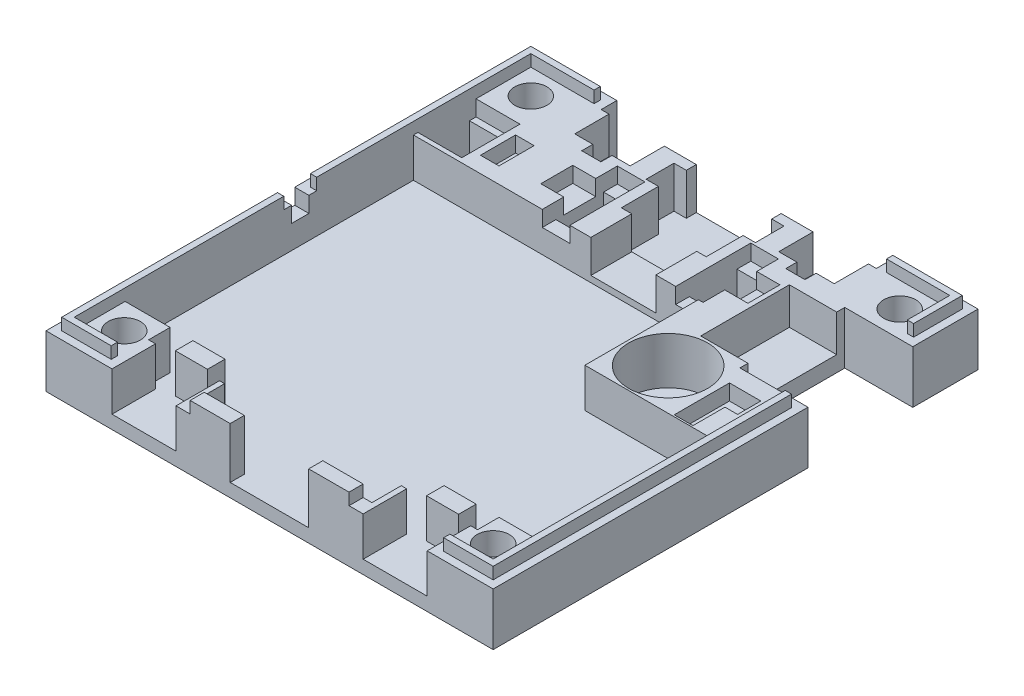
SolidWorks part; units mm, degrees
ref_plane "前视基准面" through (0, 0, 0) normal (0, 0, 1) x (1, 0, 0)
ref_plane "上视基准面" through (0, 0, 0) normal (0, 1, 0) x (1, 0, 0)
ref_plane "右视基准面" through (0, 0, 0) normal (1, 0, 0) x (0, 0, -1)
other "Configuration Table"
sketch "草图1" plane through (0, 0, 0) normal (0, 1, 0) x (1, 0, 0)
  line L1 (-21.6816, 44.1559) -> (35.2931, 44.1559)
  line L2 (-21.6816, 44.1559) -> (-21.6816, -17.6188)
  line L3 (-21.6816, -17.6188) -> (35.2931, -17.6188)
  line L4 (35.2931, 44.1559) -> (35.2931, -17.6188)
  line L10 (-19.6816, -15.6188) -> (33.2931, -15.6188)
  line L11 (-19.6816, 42.1559) -> (-19.6816, -15.6188)
  line L12 (33.2931, 42.1559) -> (-19.6816, 42.1559)
  line L13 (33.2931, -15.6188) -> (33.2931, 42.1559)
  line L14 (-19.6816, -15.6188) -> (33.2931, -15.6188) construction
  line L15 (-19.6816, 42.1559) -> (-19.6816, -15.6188) construction
  line L16 (33.2931, 42.1559) -> (-19.6816, 42.1559) construction
  line L17 (33.2931, -15.6188) -> (33.2931, 42.1559) construction
  point P0 (0, 0)
  dimension "D2" = 2
  dimension "D3" = 2
  dimension "D4" = 2
  dimension "D5" = 2
  dimension "D1" = 0
extrude "凸台-拉伸1" add sketch "草图1" along normal blind 6.7
sketch "草图2" plane through (0, 6.7, 0) normal (0, 1, 0) x (1, 0, 0)
  line L0 (25.7718, 29.0769) -> (25.7718, 24.5122) construction
  line L1 (25.9439, 22.6915) -> (33.2931, 22.6915) construction
  line L2 (33.2931, 35.6455) -> (25.8931, 35.6455) construction
  line L3 (25.7718, 29.0769) -> (25.7718, 24.5122) construction
  line L4 (25.9439, 22.6915) -> (33.2931, 22.6915) construction
  line L5 (33.2931, 35.6455) -> (25.8931, 35.6455) construction
  line L6 (35.2931, 22.4915) -> (26.6238, 22.4915)
  line L7 (35.2931, -17.6188) -> (35.2931, 44.1559) construction
  line L8 (26.6238, 22.4915) -> (26.6238, 35.8455)
  line L9 (26.6238, 35.8455) -> (35.2931, 35.8455)
  line L10 (35.2931, 22.4915) -> (35.2931, 35.8455)
  dimension "D1" = 0.2
  dimension "D2" = 0.2
  dimension "D3" = 0.3
extrude "切除-拉伸1" cut sketch "草图2" against normal through all
sketch "草图3" plane through (0, 6.7, 0) normal (0, 1, 0) x (1, 0, 0)
  line L0 (26.6238, 23.5185) -> (20.5988, 23.5185)
  line L1 (26.6238, 35.8455) -> (26.6238, 22.4915) construction
  line L2 (20.5988, 23.5185) -> (20.5988, 34.8186)
  line L3 (20.5988, 34.8186) -> (26.6238, 34.8186)
  line L4 (26.6238, 34.8186) -> (26.6238, 23.5185)
  line L5 (20.8988, 32.2066) -> (20.8988, 37.3055) construction
  line L6 (21.9488, 34.5186) -> (23.1488, 34.5186) construction
  line L7 (23.1488, 23.8185) -> (21.9488, 23.8185) construction
  dimension "D1" = 0.3
  dimension "D2" = 0.3
  dimension "D3" = 0.3
extrude "切除-拉伸2" cut sketch "草图3" against normal blind 4.7
sketch "草图4" plane through (0, 6.7, 0) normal (0, 1, 0) x (1, 0, 0)
  circle A0 centre (21.8058, 18.1684) radius 5.03
  arc A2 (20.8058, 18.1684) -> (22.8058, 18.1684) centre (21.8058, 18.1684) ccw
  arc A3 (22.8058, 18.1684) -> (20.8058, 18.1684) centre (21.8058, 18.1684) ccw
  arc A4 (20.8058, 18.1684) -> (22.8058, 18.1684) centre (21.8058, 18.1684) ccw construction
  arc A5 (22.8058, 18.1684) -> (20.8058, 18.1684) centre (21.8058, 18.1684) ccw construction
  spline S2 degree 2 poles (1990.58, 337.6383) (3.6905, 85.0515) (17.1696, 17.246) (17.2603, 16.7899) (17.4386, 16.3592) (17.6165, 15.9296) (17.8754, 15.542) (18.1338, 15.1553) (18.4633, 14.8257) (18.7921, 14.4969) (19.1796, 14.2379) (19.5662, 13.9795) (19.9968, 13.801) (20.4264, 13.623) (20.8836, 13.532) (21.3397, 13.4413) (21.8058, 13.4412) (22.2708, 13.4412) (22.7279, 13.532) (23.184, 13.6227) (23.6147, 13.801) (24.0443, 13.9789) (24.4319, 14.2379) (24.8186, 14.4962) (25.1482, 14.8257) (25.4771, 15.1545) (25.7361, 15.542) (25.9945, 15.9286) (26.1729, 16.3592) (26.3509, 16.7888) (26.4419, 17.246) (39.9075, 84.9009) (-1942.9695, 361.3773) knots -9.212791 -9.212791 -9.212791 0.0625 0.0625 0.125 0.125 0.1875 0.1875 0.25 0.25 0.3125 0.3125 0.375 0.375 0.4375 0.4375 0.5 0.5 0.5625 0.5625 0.625 0.625 0.6875 0.6875 0.75 0.75 0.8125 0.8125 0.875 0.875 0.9375 0.9375 10.203452 10.203452 10.203452 only from (17.0788, 18.1682) to (26.5327, 18.1682)
  spline S3 degree 2 poles (-1946.9685, -301.3019) (39.921, -48.7151) (26.4419, 19.0904) (26.3512, 19.5464) (26.1729, 19.9771) (25.995, 20.4067) (25.7361, 20.7943) (25.4778, 21.181) (25.1482, 21.5106) (24.8194, 21.8395) (24.4319, 22.0985) (24.0453, 22.3569) (23.6147, 22.5353) (23.1851, 22.7133) (22.7279, 22.8043) (22.2719, 22.8951) (21.8058, 22.8951) (21.3408, 22.8952) (20.8836, 22.8043) (20.4275, 22.7136) (19.9968, 22.5353) (19.5672, 22.3574) (19.1796, 22.0985) (18.7929, 21.8402) (18.4633, 21.5106) (18.1345, 21.1819) (17.8754, 20.7943) (17.6171, 20.4077) (17.4386, 19.9771) (17.2606, 19.5475) (17.1696, 19.0904) (3.7041, -48.5645) (1986.581, -325.0409) knots -9.212791 -9.212791 -9.212791 0.0625 0.0625 0.125 0.125 0.1875 0.1875 0.25 0.25 0.3125 0.3125 0.375 0.375 0.4375 0.4375 0.5 0.5 0.5625 0.5625 0.625 0.625 0.6875 0.6875 0.75 0.75 0.8125 0.8125 0.875 0.875 0.9375 0.9375 10.203452 10.203452 10.203452 only from (26.5327, 18.1682) to (17.0788, 18.1682)
  spline S4 degree 2 poles (17.0788, 18.1682) (17.0788, 17.7029) (17.1696, 17.246) (17.2603, 16.7899) (17.4386, 16.3592) (17.6165, 15.9296) (17.8754, 15.542) (18.1338, 15.1553) (18.4633, 14.8257) (18.7921, 14.4969) (19.1796, 14.2379) (19.5662, 13.9795) (19.9968, 13.801) (20.4264, 13.623) (20.8836, 13.532) (21.3397, 13.4413) (21.8058, 13.4412) (22.2708, 13.4412) (22.7279, 13.532) (23.184, 13.6227) (23.6147, 13.801) (24.0443, 13.9789) (24.4319, 14.2379) (24.8186, 14.4962) (25.1482, 14.8257) (25.4771, 15.1545) (25.7361, 15.542) (25.9945, 15.9286) (26.1729, 16.3592) (26.3509, 16.7888) (26.4419, 17.246) (26.5327, 17.7023) (26.5327, 18.1682) knots 0 0 0 0.0625 0.0625 0.125 0.125 0.1875 0.1875 0.25 0.25 0.3125 0.3125 0.375 0.375 0.4375 0.4375 0.5 0.5 0.5625 0.5625 0.625 0.625 0.6875 0.6875 0.75 0.75 0.8125 0.8125 0.875 0.875 0.9375 0.9375 1 1 1 construction
  spline S5 degree 2 poles (26.5327, 18.1682) (26.5327, 18.6335) (26.4419, 19.0904) (26.3512, 19.5464) (26.1729, 19.9771) (25.995, 20.4067) (25.7361, 20.7943) (25.4778, 21.181) (25.1482, 21.5106) (24.8194, 21.8395) (24.4319, 22.0985) (24.0453, 22.3569) (23.6147, 22.5353) (23.1851, 22.7133) (22.7279, 22.8043) (22.2719, 22.8951) (21.8058, 22.8951) (21.3408, 22.8952) (20.8836, 22.8043) (20.4275, 22.7136) (19.9968, 22.5353) (19.5672, 22.3574) (19.1796, 22.0985) (18.7929, 21.8402) (18.4633, 21.5106) (18.1345, 21.1819) (17.8754, 20.7943) (17.6171, 20.4077) (17.4386, 19.9771) (17.2606, 19.5475) (17.1696, 19.0904) (17.0788, 18.634) (17.0788, 18.1682) knots 0 0 0 0.0625 0.0625 0.125 0.125 0.1875 0.1875 0.25 0.25 0.3125 0.3125 0.375 0.375 0.4375 0.4375 0.5 0.5 0.5625 0.5625 0.625 0.625 0.6875 0.6875 0.75 0.75 0.8125 0.8125 0.875 0.875 0.9375 0.9375 1 1 1 construction
  dimension "D3" = 10.06
  dimension "D1" = 0
  dimension "D2" = 0
extrude "切除-拉伸3" cut sketch "草图4" against normal blind 6
sketch "草图5" plane through (0, 6.7, 0) normal (0, 1, 0) x (1, 0, 0)
  circle A0 centre (21.8058, 18.1684) radius 1
  dimension "D1" = 2
extrude "切除-拉伸4" cut sketch "草图5" against normal through all
sketch "草图6" plane through (0, 6.7, 0) normal (0, 1, 0) x (1, 0, 0)
  line L0 (29.9991, 13.1312) -> (27.6125, 13.1312)
  line L1 (27.6125, 13.1312) -> (27.6125, 20.171)
  line L2 (27.6125, 20.171) -> (31.6082, 20.171)
  line L3 (31.6082, 20.171) -> (31.6082, 17.212)
  line L4 (31.6082, 17.212) -> (29.9991, 17.212)
  line L5 (29.9991, 13.1312) -> (29.9991, 17.212)
  line L6 (27.8125, 14.6923) -> (27.8125, 13.4074) construction
  line L7 (29.7991, 15.6447) -> (29.7991, 16.9297) construction
  line L8 (27.8887, 13.3312) -> (29.7229, 13.3312) construction
  line L9 (29.1808, 17.412) -> (29.1058, 17.412) construction
  line L10 (31.4082, 18.4423) -> (31.4082, 19.8948) construction
  line L11 (31.332, 19.971) -> (30.3004, 19.971) construction
  dimension "D1" = 0.2
  dimension "D2" = 0.2
  dimension "D3" = 0.2
  dimension "D4" = 0.2
  dimension "D5" = 0.2
  dimension "D6" = 0.2
extrude "切除-拉伸5" cut sketch "草图6" against normal blind 2
sketch "草图7" plane through (0, 6.7, 0) normal (0, 1, 0) x (1, 0, 0)
  line L0 (13.5357, 27.3736) -> (17.0497, 27.3736)
  line L1 (17.0497, 27.3736) -> (17.0497, 30.1312)
  line L2 (17.0497, 30.1312) -> (19.9991, 30.1312)
  line L3 (19.9991, 30.1312) -> (19.9991, 34.2059)
  line L4 (19.9991, 34.2059) -> (17.0497, 34.2059)
  line L5 (17.0497, 34.2059) -> (17.0497, 36.9636)
  line L6 (17.0497, 36.9636) -> (13.5357, 36.9636)
  line L7 (13.5357, 36.9636) -> (13.5357, 27.3736)
  line L8 (15.7558, 36.6636) -> (14.8558, 36.6636) construction
  line L9 (14.8558, 27.6736) -> (15.4302, 27.6736) construction
  line L10 (16.8497, 29.4596) -> (16.8497, 34.8686) construction
  line L11 (17.8887, 30.3312) -> (19.7229, 30.3312) construction
  line L12 (19.7229, 34.0059) -> (17.8887, 34.0059) construction
  line L13 (19.7991, 32.6448) -> (19.7991, 33.9297) construction
  line L14 (0.0497, 27.3736) -> (0.0497, 36.9636)
  line L15 (0.0497, 36.9636) -> (-3.4643, 36.9636)
  line L16 (0.0497, 27.3736) -> (-3.4643, 27.3736)
  line L17 (-3.4643, 27.3736) -> (-3.4643, 30.1312)
  line L18 (-3.4643, 30.1312) -> (-6.3876, 30.1312)
  line L19 (-6.3876, 30.1312) -> (-6.3876, 34.2059)
  line L20 (-6.3876, 34.2059) -> (-3.4643, 34.2059)
  line L21 (-3.4643, 34.2059) -> (-3.4643, 36.9636)
  line L22 (-1.2443, 36.6636) -> (-2.1443, 36.6636) construction
  line L23 (-2.1443, 27.6736) -> (-1.2443, 27.6736) construction
  line L24 (-0.1503, 29.4596) -> (-0.1503, 34.8686) construction
  line L25 (-3.2643, 34.8776) -> (-3.2643, 29.5535) construction
  line L26 (-4.2772, 34.0059) -> (-6.1114, 34.0059) construction
  line L27 (-6.1876, 31.6924) -> (-6.1876, 30.4074) construction
  line L28 (-6.1114, 30.3312) -> (-4.2772, 30.3312) construction
  dimension "D1" = 0.3
  dimension "D2" = 0.3
  dimension "D3" = 0.2
  dimension "D4" = 0.2
  dimension "D5" = 0.2
  dimension "D6" = 0.2
  dimension "D7" = 0.2
  dimension "D8" = 0.2
  dimension "D9" = 0.3
  dimension "D10" = 0.3
  dimension "D11" = 0.2
  dimension "D12" = 0.2
  dimension "D13" = 0.2
  dimension "D14" = 0.2
  dimension "D15" = 0.2
  dimension "D16" = 0.2
extrude "切除-拉伸6" cut sketch "草图7" against normal blind 2
sketch "草图8" plane through (0, 6.7, 0) normal (0, 1, 0) x (1, 0, 0)
  line L0 (17.0497, 27.3736) -> (17.0497, 30.1312) construction
  line L1 (17.0497, 29.129) -> (13.5357, 29.129)
  line L2 (17.0497, 29.129) -> (17.0497, 35.2046)
  line L3 (17.0497, 35.2046) -> (13.5357, 35.2046)
  line L4 (13.5357, 29.129) -> (13.5357, 35.2046)
  line L5 (13.5357, 36.9636) -> (13.5357, 27.3736) construction
  line L6 (13.8538, 29.3326) -> (16.7227, 29.3326) construction
  line L7 (16.7128, 35.0046) -> (13.8627, 35.0046) construction
  line L8 (0.0497, 27.3736) -> (0.0497, 36.9636) construction
  line L9 (0.0497, 29.129) -> (-3.4643, 29.129)
  line L10 (0.0497, 29.129) -> (0.0497, 35.2046)
  line L11 (0.0497, 35.2046) -> (-3.4643, 35.2046)
  line L12 (-3.4643, 29.129) -> (-3.4643, 35.2046)
  line L13 (-3.4643, 36.9636) -> (-3.4643, 34.2059) construction
  line L14 (-3.1463, 29.3326) -> (-0.2773, 29.3326) construction
  line L15 (-0.2873, 35.0046) -> (-3.1373, 35.0046) construction
  dimension "D1" = 0.2036
  dimension "D2" = 0.2
  dimension "D3" = 0.2036
  dimension "D4" = 0.2
extrude "切除-拉伸7" cut sketch "草图8" against normal through all
sketch "草图9" plane through (0, 6.7, 0) normal (0, 1, 0) x (1, 0, 0)
  line L0 (23.3374, 37.7935) -> (23.3374, 42.1559)
  line L1 (-19.6816, 42.1559) -> (33.2931, 42.1559) construction
  line L2 (23.3374, 42.1559) -> (16.2744, 42.1559)
  line L3 (16.2744, 42.1559) -> (16.2744, 37.7935)
  line L4 (16.2744, 37.7935) -> (23.3374, 37.7935)
  line L6 (16.5744, 39.0234) -> (16.5744, 41.8105) construction
  line L8 (23.0374, 41.8105) -> (23.0374, 39.0234) construction
  line L9 (16.9678, 37.9935) -> (18.6497, 37.9935) construction
  line L10 (-2.6626, 42.1559) -> (-2.6626, 37.7935)
  line L11 (-2.6626, 37.7935) -> (-9.7257, 37.7935)
  line L12 (-9.7257, 37.7935) -> (-9.7257, 42.1559)
  line L13 (-9.7257, 42.1559) -> (-2.6626, 42.1559)
  line L14 (-9.0322, 37.9935) -> (-7.3503, 37.9935) construction
  line L15 (-9.4257, 39.0234) -> (-9.4257, 41.8105) construction
  line L16 (-2.9626, 41.8105) -> (-2.9626, 39.0234) construction
  dimension "D1" = 0.3
  dimension "D2" = 0.3
  dimension "D3" = 0.2
  dimension "D4" = 0.2
  dimension "D5" = 0.3
  dimension "D6" = 0.3
extrude "切除-拉伸8" cut sketch "草图9" against normal blind 4.7
sketch "草图10" plane through (0, 6.7, 0) normal (0, 1, 0) x (1, 0, 0)
  line L0 (21.0307, 37.7935) -> (21.0307, 36.3735)
  line L1 (16.2744, 37.7935) -> (23.3374, 37.7935) construction
  line L2 (21.0307, 36.3735) -> (18.5808, 36.3735)
  line L3 (18.5808, 36.3735) -> (18.5808, 37.7935)
  line L4 (18.5808, 37.7935) -> (21.0307, 37.7935)
  line L5 (-4.9693, 37.7935) -> (-4.9693, 36.3735)
  line L6 (-9.7257, 37.7935) -> (-2.6626, 37.7935) construction
  line L7 (-4.9693, 36.3735) -> (-7.4193, 36.3735)
  line L8 (-7.4193, 36.3735) -> (-7.4193, 37.7935)
  line L9 (-7.4193, 37.7935) -> (-4.9693, 37.7935)
  line L10 (18.8808, 37.2906) -> (18.8808, 36.6735) construction
  line L11 (20.7307, 37.5771) -> (20.7307, 38.3735) construction
  line L12 (18.8808, 36.6735) -> (19.4808, 36.6735) construction
  line L13 (-7.1193, 38.3735) -> (-7.1193, 37.5771) construction
  line L14 (-5.2693, 36.6735) -> (-5.2693, 37.2735) construction
  line L15 (-6.7873, 36.6735) -> (-6.5193, 36.6735) construction
  dimension "D1" = 0.3
  dimension "D2" = 0.3
  dimension "D3" = 0.3
  dimension "D4" = 0.3
  dimension "D5" = 0.3
  dimension "D6" = 0.3
extrude "切除-拉伸9" cut sketch "草图10" against normal blind 2
sketch "草图11" plane through (0, 6.7, 0) normal (0, 1, 0) x (1, 0, 0)
  line L0 (24.3374, 42.1559) -> (24.3374, 44.1559)
  line L1 (-19.6816, 42.1559) -> (33.2931, 42.1559) construction
  line L2 (35.2931, 44.1559) -> (-21.6816, 44.1559) construction
  line L3 (24.3374, 44.1559) -> (-10.7257, 44.1559)
  line L4 (-10.7257, 44.1559) -> (-10.7257, 42.1559)
  line L5 (-10.7257, 42.1559) -> (24.3374, 42.1559)
  line L6 (-9.7257, 42.1559) -> (-9.7257, 37.7935) construction
  line L7 (23.3374, 37.7935) -> (23.3374, 42.1559) construction
  dimension "D1" = 1
  dimension "D2" = 1
extrude "切除-拉伸10" cut sketch "草图11" against normal through all
sketch "草图12" plane through (0, 6.7, 0) normal (0, 1, 0) x (1, 0, 0)
  line L0 (12.2126, 42.1559) -> (12.2126, 40.9527)
  line L1 (-2.6626, 42.1559) -> (16.2744, 42.1559) construction
  line L2 (12.2126, 40.9527) -> (13.7826, 40.9527)
  line L3 (13.7826, 40.9527) -> (13.7826, 37.3079)
  line L4 (13.7826, 37.3079) -> (12.2126, 37.3079)
  line L5 (12.2126, 37.3079) -> (12.2126, 32.6056)
  line L6 (12.2126, 32.6056) -> (1.3986, 32.6056)
  line L7 (1.3986, 32.6056) -> (1.3986, 37.3333)
  line L8 (1.3986, 37.3333) -> (-0.1714, 37.3333)
  line L9 (-0.1714, 37.3333) -> (-0.1714, 40.8829)
  line L10 (-0.1714, 40.8829) -> (1.4009, 40.8829)
  line L11 (1.4009, 40.8829) -> (1.4009, 42.1559)
  line L12 (1.7257, 32.8056) -> (2.8687, 32.8056) construction
  line L13 (0.1556, 37.5333) -> (1.5986, 37.5333) construction
  line L14 (1.4009, 42.1559) -> (12.2126, 42.1559)
  dimension "D1" = 0.2
  dimension "D2" = 0.2
  dimension "D3" = 0.2
  dimension "D4" = 0.2
  dimension "D5" = 0.2
  dimension "D6" = 0.2
  dimension "D7" = 0.2
  dimension "D8" = 0.2
  dimension "D9" = 0.2
  dimension "D10" = 0.2
  dimension "D11" = 0.2
extrude "切除-拉伸11" cut sketch "草图12" against normal blind 5.3
sketch "草图13" plane through (0, 6.7, 0) normal (0, 1, 0) x (1, 0, 0)
  line L0 (11.0123, 32.6056) -> (11.0123, 27.369)
  line L1 (1.3986, 32.6056) -> (12.2126, 32.6056) construction
  line L2 (11.0123, 27.369) -> (2.7262, 27.369)
  line L3 (2.7262, 27.369) -> (2.7262, 32.6056)
  line L4 (2.7262, 32.6056) -> (11.0123, 32.6056)
  line L5 (9.3057, 29.0756) -> (9.3057, 27.569) construction
  line L7 (9.3057, 29.0756) -> (10.8123, 29.0756)
  line L8 (6.8692, 32.6056) -> (6.8692, 27.369) construction
  line L9 (5.7897, 31.0276) -> (5.7897, 32.9326) construction
  line L10 (7.9487, 31.0276) -> (7.9487, 32.9326) construction
  circle A0 centre (9.3057, 29.0756) radius 1.5065 construction
  dimension "D1" = 0.2
  dimension "D2" = 0.2
extrude "切除-拉伸12" cut sketch "草图13" against normal blind 4.2
sketch "草图14" plane through (0, 6.7, 0) normal (0, 1, 0) x (1, 0, 0)
  line L0 (-11.0145, 29.4288) -> (-11.0145, 33.9084)
  line L1 (-11.0145, 33.9084) -> (-13.3741, 33.9084)
  line L2 (-13.3741, 33.9084) -> (-13.3741, 29.4288)
  line L3 (-13.3741, 29.4288) -> (-11.0145, 29.4288)
  line L4 (-12.9455, 29.6288) -> (-11.4431, 29.6288) construction
  line L5 (-13.1741, 33.4798) -> (-13.1741, 32.0698) construction
  line L6 (-11.2145, 32.0698) -> (-11.2145, 33.4798) construction
  line L7 (-11.4431, 33.7084) -> (-12.9455, 33.7084) construction
  line L8 (-14.2873, 27.962) -> (-14.2873, 35.3751)
  line L9 (-14.2873, 35.3751) -> (-19.8816, 35.3751)
  line L10 (-19.8816, 35.3751) -> (-19.8816, 27.962)
  line L11 (-19.8816, 27.962) -> (-14.2873, 27.962)
  line L12 (-14.9542, 28.262) -> (-16.1542, 28.262) construction
  line L13 (-16.1542, 35.0751) -> (-14.9542, 35.0751) construction
  line L14 (-14.4873, 29.1286) -> (-14.4873, 34.2087) construction
  line L15 (-19.6816, -15.6188) -> (-19.6816, 42.1559) construction
  dimension "D1" = 0.2
  dimension "D2" = 0.2
  dimension "D3" = 0.2
  dimension "D4" = 0.2
  dimension "D5" = 0.3
  dimension "D6" = 0.3
  dimension "D7" = 0.2
  dimension "D8" = 0.2
extrude "切除-拉伸13" cut sketch "草图14" against normal blind 2
sketch "草图15" plane through (0, 6.7, 0) normal (0, 1, 0) x (1, 0, 0)
  line L0 (-14.2873, 28.8016) -> (-19.8816, 28.8016)
  line L1 (-14.2873, 27.962) -> (-14.2873, 35.3751) construction
  line L2 (-19.8816, 35.3751) -> (-19.8816, 27.962) construction
  line L3 (-19.8816, 28.8016) -> (-19.8816, 34.5357)
  line L4 (-19.8816, 34.5357) -> (-14.2873, 34.5357)
  line L5 (-14.2873, 34.5357) -> (-14.2873, 28.8016)
  line L6 (-17.9231, 29.0016) -> (-16.3854, 29.0016) construction
  line L7 (-16.3854, 34.3357) -> (-17.9231, 34.3357) construction
  dimension "D1" = 0.2
  dimension "D2" = 0.2
extrude "切除-拉伸14" cut sketch "草图15" against normal through all
sketch "草图16" plane through (0, 6.7, 0) normal (0, 1, 0) x (1, 0, 0)
  line L0 (16.4498, 27.3956) -> (-19.8816, 27.3956)
  line L1 (-19.8816, 27.3956) -> (-19.8816, -9.3405)
  line L2 (-19.8816, -9.3405) -> (-4.4678, -9.3405)
  line L3 (-4.4678, -9.3405) -> (-4.4678, -15.8188)
  line L4 (-4.4678, -15.8188) -> (1.7887, -15.8188)
  line L5 (18.0453, -15.8188) -> (18.0453, -9.3405)
  line L6 (18.0453, -9.3405) -> (33.4931, -9.3405)
  line L7 (33.4931, -9.3405) -> (33.4931, 12.9135)
  line L8 (33.4931, 12.9135) -> (16.4498, 12.9135)
  line L9 (16.4498, 12.9135) -> (16.4498, 27.3956)
  line L10 (17.5453, -13.2615) -> (17.5453, -14.7855) construction
  line L11 (-3.9678, -14.7855) -> (-3.9678, -13.2615) construction
  line L12 (-19.6816, -8.8405) -> (-4.6943, -8.8405) construction
  line L13 (-19.6816, -15.6188) -> (-19.6816, 42.1559) construction
  line L15 (15.8228, 26.7956) -> (-2.1773, 26.7956) construction
  line L17 (15.9498, 13.6685) -> (15.9498, 26.6686) construction
  line L18 (33.2931, 12.4135) -> (18.3058, 12.4135) construction
  line L19 (33.2931, 42.1559) -> (33.2931, -15.6188) construction
  line L20 (18.3058, -8.8405) -> (33.2931, -8.8405) construction
  line L21 (33.2931, -15.6188) -> (-19.6816, -15.6188) construction
  line L22 (1.7887, -15.8188) -> (1.7887, -17.6188)
  line L23 (-21.6816, -17.6188) -> (35.2931, -17.6188) construction
  line L24 (1.7887, -17.6188) -> (11.7887, -17.6188)
  line L25 (11.7887, -17.6188) -> (11.7887, -15.8188)
  line L26 (6.7887, 12.4135) -> (6.7887, -21.6188) construction
  line L27 (15.7888, 12.4135) -> (-2.2113, 12.4135) construction
  line L28 (11.7887, -15.8188) -> (18.0453, -15.8188)
  dimension "D1" = 0.5
  dimension "D2" = 0.5
  dimension "D3" = 0.5
  dimension "D4" = 0.2
  dimension "D5" = 0.6
  dimension "D6" = 0.5
  dimension "D7" = 0.5
  dimension "D8" = 0.2
  dimension "D9" = 0.5
  dimension "D10" = 0.2
  dimension "D11" = 10
extrude "切除-拉伸15" cut sketch "草图16" against normal blind 5
sketch "草图18" plane through (0, 6.7, 0) normal (0, 1, 0) x (1, 0, 0)
  line L0 (-5.1172, -17.6188) -> (-13.2712, -17.6188)
  line L1 (-21.6816, -17.6188) -> (1.7887, -17.6188) construction
  line L2 (-13.2712, -17.6188) -> (-13.2712, -11.5781)
  line L3 (-13.2712, -11.5781) -> (-5.1172, -11.5781)
  line L4 (-5.1172, -11.5781) -> (-5.1172, -17.6188)
  line L5 (-12.9712, -11.7026) -> (-12.9712, -15.5814) construction
  line L6 (-5.4172, -15.5814) -> (-5.4172, -11.7026) construction
  line L7 (-5.6712, -11.8781) -> (-12.7172, -11.8781) construction
  line L8 (26.8829, -17.6188) -> (26.8829, -11.5781)
  line L9 (11.7887, -17.6188) -> (35.2931, -17.6188) construction
  line L10 (26.8829, -11.5781) -> (18.7289, -11.5781)
  line L11 (18.7289, -11.5781) -> (18.7289, -17.6188)
  line L12 (18.7289, -17.6188) -> (26.8829, -17.6188)
  line L13 (19.0289, -11.7026) -> (19.0289, -15.5814) construction
  line L14 (26.5829, -15.5814) -> (26.5829, -11.7026) construction
  line L15 (26.3289, -11.8781) -> (19.2829, -11.8781) construction
  dimension "D1" = 0.3
  dimension "D2" = 0.3
  dimension "D3" = 0.3
  dimension "D4" = 0.3
  dimension "D5" = 0.3
  dimension "D6" = 0.3
extrude "切除-拉伸16" cut sketch "草图18" against normal blind 5
sketch "草图19" plane through (0, 6.7, 0) normal (0, 1, 0) x (1, 0, 0)
  line L0 (-4.4678, -9.3405) -> (-4.4678, -15.8188) construction
  line L1 (-4.4678, -12.0781) -> (-7.1508, -12.0781)
  line L2 (-4.4678, -12.0781) -> (-4.4678, -9.3405)
  line L3 (-4.4678, -9.3405) -> (-7.1508, -9.3405)
  line L4 (-7.1508, -12.0781) -> (-7.1508, -9.3405)
  line L5 (-19.8816, -9.3405) -> (-4.4678, -9.3405) construction
  line L6 (18.0453, -9.3405) -> (33.4931, -9.3405) construction
  line L7 (-11.2378, -9.3405) -> (-14.1508, -9.3405)
  line L8 (-11.2378, -9.3405) -> (-11.2378, -12.0781)
  line L9 (-11.2378, -12.0781) -> (-14.1508, -12.0781)
  line L10 (-14.1508, -9.3405) -> (-14.1508, -12.0781)
  line L11 (18.0453, -9.3405) -> (20.7623, -9.3405)
  line L12 (18.0453, -9.3405) -> (18.0453, -12.0781)
  line L13 (18.0453, -12.0781) -> (20.7623, -12.0781)
  line L14 (20.7623, -9.3405) -> (20.7623, -12.0781)
  line L15 (24.8492, -9.3405) -> (27.7623, -9.3405)
  line L16 (24.8492, -9.3405) -> (24.8492, -12.0781)
  line L17 (24.8492, -12.0781) -> (27.7623, -12.0781)
  line L18 (27.7623, -9.3405) -> (27.7623, -12.0781)
  dimension "D1" = 0.3
  dimension "D2" = 0.2
  dimension "D3" = 0.2
  dimension "D4" = 0.3
  dimension "D5" = 0.3
  dimension "D6" = 0.3
  dimension "D7" = 0.2
  dimension "D8" = 0.2
  dimension "D9" = 0.3
  dimension "D10" = 0.3
extrude "切除-拉伸17" cut sketch "草图19" against normal blind 5
sketch "草图24" plane through (0, 6.7, 0) normal (0, 1, 0) x (1, 0, 0)
  line L0 (-11.8257, 42.3559) -> (-19.8816, 42.3559)
  line L1 (-19.6816, 12.4135) -> (-18.6038, 12.4135) construction
  line L2 (-19.8816, 42.3559) -> (-19.8816, 15.0765)
  line L3 (-19.8816, -15.8188) -> (-14.3712, -15.8188)
  line L4 (33.4931, -15.8188) -> (33.4931, 21.3915)
  line L5 (26.6238, 22.4915) -> (35.2931, 22.4915) construction
  line L6 (33.4931, 22.4915) -> (34.2931, 22.4915) construction
  line L7 (34.2931, 21.3915) -> (34.2931, -16.6188)
  line L8 (34.2931, -16.6188) -> (27.9829, -16.6188)
  line L9 (-20.6816, -16.6188) -> (-20.6816, 10.8765)
  line L10 (-20.6816, 43.1559) -> (-11.8257, 43.1559)
  line L12 (-19.6816, -15.6188) -> (-19.6816, 42.1559) construction
  line L13 (-19.6816, 42.1559) -> (33.2931, 42.1559) construction
  line L14 (-4.6943, 12.4135) -> (-19.6816, 12.4135) construction
  line L15 (33.2931, 42.1559) -> (33.2931, -15.6188) construction
  line L16 (33.4931, 36.9455) -> (33.4931, 42.3559)
  line L17 (35.2931, 35.8455) -> (26.6238, 35.8455) construction
  line L18 (33.4931, 42.3559) -> (25.4374, 42.3559)
  line L19 (-18.6038, 13.5415) -> (-19.6816, 13.5415) construction
  line L21 (25.4374, 43.1559) -> (34.2931, 43.1559)
  line L22 (34.2931, 43.1559) -> (34.2931, 36.9455)
  line L23 (34.2931, 35.8455) -> (33.4931, 35.8455) construction
  line L24 (-19.8816, 15.0765) -> (-20.6816, 15.0765)
  line L25 (-19.8816, 10.8765) -> (-20.6816, 10.8765)
  line L27 (-19.1943, 13.5415) -> (-4.1943, 13.5415) construction
  line L28 (-20.6816, 15.0765) -> (-20.6816, 43.1559)
  line L29 (-19.8816, 10.8765) -> (-19.8816, -15.8188)
  line L30 (-13.2712, -16.6188) -> (-13.2712, -15.8188) construction
  line L31 (-13.2712, -12.0781) -> (-13.2712, -17.6188) construction
  line L33 (-19.6816, 12.9765) -> (-18.7049, 12.9765) construction
  line L34 (1.7887, -16.6188) -> (1.7887, -15.8188)
  line L35 (1.7887, -15.8188) -> (1.7887, -17.6188) construction
  line L36 (11.7887, -16.6188) -> (11.7887, -15.8188)
  line L37 (11.7887, -17.6188) -> (11.7887, -15.8188) construction
  line L40 (26.8829, -17.6188) -> (26.8829, -12.0781) construction
  line L41 (26.8829, -16.6188) -> (26.8829, -15.8188) construction
  line L42 (-14.3712, -16.6188) -> (-20.6816, -16.6188)
  line L43 (-3.3139, -15.8188) -> (1.7887, -15.8188)
  line L45 (11.7887, -15.8188) -> (16.9254, -15.8188)
  line L47 (27.9829, -15.8188) -> (33.4931, -15.8188)
  line L48 (11.7887, -17.6188) -> (18.7289, -17.6188) construction
  line L50 (11.7887, -16.6188) -> (11.7887, -17.6188)
  line L51 (11.7887, -17.6188) -> (16.9254, -17.6188)
  line L52 (16.9254, -15.8188) -> (16.9254, -17.6188)
  line L53 (-3.5139, -13.2542) -> (-3.5139, -17.6188) construction
  line L54 (1.7887, -17.6188) -> (-3.3139, -17.6188)
  line L55 (1.7887, -17.6188) -> (1.7887, -16.6188)
  line L57 (-3.3139, -17.6188) -> (-3.3139, -15.8188)
  line L58 (17.1254, -13.2288) -> (17.1254, -17.6188) construction
  line L60 (25.4374, 43.1559) -> (25.4374, 42.3559)
  line L61 (-11.8257, 43.1559) -> (-11.8257, 42.3559)
  line L62 (-10.7257, 44.1559) -> (-10.7257, 42.1559) construction
  line L63 (24.3374, 42.1559) -> (24.3374, 44.1559) construction
  line L64 (27.9829, -15.8188) -> (27.9829, -16.6188)
  line L65 (-14.3712, -15.8188) -> (-14.3712, -16.6188)
  line L66 (33.4931, 21.3915) -> (34.2931, 21.3915)
  line L67 (33.4931, 36.9455) -> (34.2931, 36.9455)
  dimension "D1" = 0.2
  dimension "D2" = 0.2
  dimension "D3" = 0.2
  dimension "D4" = 0.2
  dimension "D5" = 0.8
  dimension "D6" = 0.8
  dimension "D7" = 0.8
  dimension "D8" = 0.8
  dimension "D9" = 0.8
  dimension "D10" = 0.8
  dimension "D11" = 0.2
  dimension "D12" = 4.2
  dimension "D13" = 0.565
  dimension "D14" = 0.2
  dimension "D15" = 1.1
  dimension "D16" = 1.1
  dimension "D17" = 1.1
  dimension "D18" = 1.1
  dimension "D19" = 1.1
  dimension "D20" = 1.1
  dimension "D21" = 0.8
  dimension "D22" = 0.8
  dimension "D23" = 0.2
extrude "凸台-拉伸4" add sketch "草图24" along normal blind 1.5
sketch "草图25" plane through (0, 6.7, 0) normal (0, 1, 0) x (1, 0, 0)
  circle A0 centre (30.3058, 39.1686) radius 1.8565 construction
  circle A1 centre (-16.6943, 39.1686) radius 1.8565 construction
  circle A2 centre (-16.6943, -12.6315) radius 1.8565 construction
  circle A3 centre (30.3058, -12.6315) radius 1.8565 construction
  circle A4 centre (30.3058, -12.6315) radius 2.05
  circle A5 centre (-16.6943, 39.1686) radius 2.05
  circle A6 centre (-16.6943, -12.6315) radius 2.05
  circle A7 centre (30.3058, 39.1686) radius 2.05
  dimension "D1" = 4.1
  dimension "D2" = 4.1
  dimension "D3" = 4.1
  dimension "D4" = 4.1
extrude "切除-拉伸18" cut sketch "草图25" against normal blind 5
sketch "草图26" plane through (-21.6816, 0, 0) normal (-1, 0, 0) x (0, 0, 1)
  line L0 (-11.8765, 6.7) -> (-11.8765, 4.7)
  line L1 (-44.1559, 6.7) -> (17.6188, 6.7) construction
  line L2 (-11.8765, 4.7) -> (-14.0765, 4.7)
  line L3 (-14.0765, 4.7) -> (-14.0765, 6.7)
  line L4 (-14.0765, 6.7) -> (-11.8765, 6.7)
  line L5 (-10.8765, 8.2) -> (-10.8765, 6.7) construction
  line L6 (-15.0765, 8.2) -> (-15.0765, 6.7) construction
  dimension "D1" = 1
  dimension "D2" = 1
  dimension "D3" = 2
extrude "切除-拉伸19" cut sketch "草图26" against normal up to next
